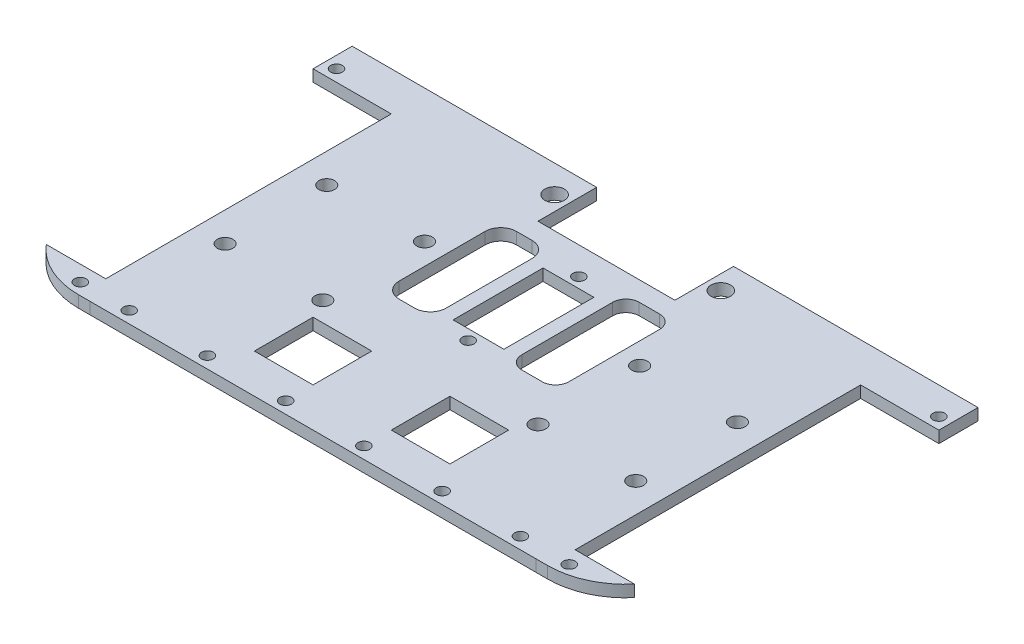
SolidWorks part; units mm, degrees
ref_plane "Alzado" through (0, 0, 0) normal (0, 0, 1) x (1, 0, 0)
ref_plane "Planta" through (0, 0, 0) normal (0, 1, 0) x (1, 0, 0)
ref_plane "Vista lateral" through (0, 0, 0) normal (1, 0, 0) x (0, 0, -1)
sketch "Croquis1" plane through (0, 0, 0) normal (0, 1, 0) x (1, 0, 0)
  line L0 (-80, 17.4769) -> (-80, -128.597) construction
  line L1 (0, 0) -> (-160, 0)
  line L2 (0, 0) -> (0, -70)
  line L3 (-20, -90) -> (-23, -90)
  line L4 (-160, 0) -> (-160, -70)
  line L5 (-101.3055, -36.199) -> (-73.3691, -36.199) construction
  line L6 (-86.5, -24.699) -> (-73.5, -24.699)
  line L7 (-86.5, -24.699) -> (-86.5, -47.699)
  line L8 (-86.5, -47.699) -> (-73.5, -47.699)
  line L9 (-73.5, -24.699) -> (-73.5, -47.699)
  line L10 (-137, -90) -> (-140, -90)
  line L12 (-137, -90) -> (-137, -89.999)
  line L13 (-137, -89.999) -> (-23, -89.999)
  line L14 (-23, -90) -> (-23, -89.999)
  line L15 (-89, -61.999) -> (-89, -81.749) construction
  line L16 (-105, -79.999) -> (-90, -79.999)
  line L17 (-105, -79.999) -> (-105, -64.999)
  line L18 (-105, -64.999) -> (-90, -64.999)
  line L19 (-90, -79.999) -> (-90, -64.999)
  line L20 (-55, -79.999) -> (-70, -79.999)
  line L21 (-55, -79.999) -> (-55, -64.999)
  line L22 (-55, -64.999) -> (-70, -64.999)
  line L23 (-70, -79.999) -> (-70, -64.999)
  circle A0 centre (-101.245, -7) radius 2.5
  circle A1 centre (-58.755, -7) radius 2.5
  circle A2 centre (-27.5, -60) radius 2
  circle A3 centre (-52.5, -60) radius 2
  circle A4 centre (-27.5, -34) radius 2
  circle A5 centre (-52.5, -34) radius 2
  circle A6 centre (-107.5, -34) radius 2
  circle A7 centre (-132.5, -34) radius 2
  circle A8 centre (-132.5, -60) radius 2
  circle A9 centre (-107.5, -60) radius 2
  circle A10 centre (-80, -22.054) radius 1.5
  circle A11 centre (-80, -50.344) radius 1.5
  arc A12 (0, -70) -> (-20, -90) centre (-20, -70) cw
  arc A13 (-140, -90) -> (-160, -70) centre (-140, -70) cw
  point P45 (-160, -90)
  dimension "D3" = 42.49
  dimension "D4" = 5
  dimension "D6" = 25
  dimension "D8" = 4
  dimension "D9" = 55
  dimension "D13" = 28.29
  dimension "D14" = 3
  dimension "D18" = 20
  dimension "D19" = 20
  dimension "D1" = 160
  dimension "D2" = 90
  dimension "D5" = 7
  dimension "D7" = 26
  dimension "D10" = 30
  dimension "D11" = 23
  dimension "D12" = 13
  dimension "D15" = 0.001
  dimension "D16" = 114
  dimension "D17" = 42.3
  dimension "D20" = 19
  dimension "D21" = 15
  dimension "D22" = 15
  dimension "D23" = 10
extrude "Saliente-Extruir1" add sketch "Croquis1" along normal blind 3
sketch "Croquis2" plane through (0, 3, 0) normal (0, 1, 0) x (1, 0, 0)
  line L0 (-160, 0) -> (-160, -70) construction
  line L1 (-160, -10) -> (-140, -10)
  line L2 (-160, -10) -> (-160, -82.999)
  line L3 (-160, -82.999) -> (-140, -82.999)
  line L4 (-140, -10) -> (-140, -82.999)
  line L5 (0, -70) -> (0, 0) construction
  line L6 (0, -10) -> (-20, -10)
  line L7 (0, -10) -> (0, -82.999)
  line L8 (0, -82.999) -> (-20, -82.999)
  line L9 (-20, -10) -> (-20, -82.999)
  line L10 (-80, 13.295) -> (-80, -109.5131) construction
  line L11 (0, 0) -> (-160, 0) construction
  line L12 (-137, -89.999) -> (-23, -89.999) construction
  dimension "D1" = 20
  dimension "D2" = 10
  dimension "D3" = 7
extrude "Cortar-Extruir1" cut sketch "Croquis2" against normal blind 10
sketch "Croquis3" plane through (0, 0, 0) normal (0, -1, 0) x (1, 0, 0)
  line L0 (0, 0) -> (-160, 0) construction
  line L1 (-97.5, 0) -> (-62.5, 0)
  line L2 (-97.5, 0) -> (-97.5, 15)
  line L3 (-97.5, 15) -> (-62.5, 15)
  line L4 (-62.5, 0) -> (-62.5, 15)
  line L5 (-80, 97.2712) -> (-80, -21.2749) construction
  line L6 (-20, 82.999) -> (-20, 10) construction
  line L7 (-140, 10) -> (-140, 82.999) construction
  dimension "D1" = 35
  dimension "D2" = 15
extrude "Cortar-Extruir2" cut sketch "Croquis3" against normal blind 10
sketch "Croquis4" plane through (0, 0, 0) normal (0, -1, 0) x (-1, 0, 0)
  line L0 (80, -96.2931) -> (80, 6.7064) construction
  line L1 (20, -82.999) -> (20, -10) construction
  line L2 (140, -10) -> (140, -82.999) construction
  line L3 (160, 0) -> (160, -10) construction
  line L4 (137, -89.999) -> (23, -89.999) construction
  line L5 (160, -10) -> (140, -10) construction
  circle A0 centre (157, -7) radius 1.5
  circle A1 centre (3, -7) radius 1.5
  circle A2 centre (30, -86.999) radius 1.5
  circle A3 centre (50, -86.999) radius 1.5
  circle A4 centre (70, -86.999) radius 1.5
  circle A5 centre (130, -86.999) radius 1.5
  circle A6 centre (90, -86.999) radius 1.5
  circle A7 centre (110, -86.999) radius 1.5
  circle A8 centre (142.5, -86.999) radius 1.5
  circle A9 centre (17.5, -86.999) radius 1.5
  dimension "D1" = 20
  dimension "D5" = 3
  dimension "D8" = 125
  dimension "D2" = 60
  dimension "D3" = 100
  dimension "D4" = 3
  dimension "D6" = 3
  dimension "D7" = 3
extrude "Cortar-Extruir3" cut sketch "Croquis4" against normal blind 10
sketch "Croquis5" plane through (0, 0, 0) normal (0, -1, 0) x (-1, 0, 0)
  line L0 (80, -99.9916) -> (80, 23.7881) construction
  line L1 (98, -50) -> (94, -50)
  line L2 (102, -46) -> (102, -24)
  line L3 (98, -20) -> (94, -20)
  line L4 (90, -46) -> (90, -24)
  line L5 (66.6138, -50) -> (61.3862, -50)
  line L6 (70, -46.6138) -> (70, -23.3862)
  line L7 (66.6138, -20) -> (61.3862, -20)
  line L8 (58, -46.6138) -> (58, -23.3862)
  line L9 (20, -82.999) -> (20, -10) construction
  line L10 (140, -10) -> (140, -82.999) construction
  line L11 (97.5, 0) -> (160, 0) construction
  arc A0 (94, -50) -> (90, -46) centre (94, -46) cw
  arc A1 (98, -50) -> (102, -46) centre (98, -46) ccw
  arc A2 (94, -20) -> (90, -24) centre (94, -24) ccw
  arc A3 (102, -24) -> (98, -20) centre (98, -24) ccw
  arc A4 (70, -23.3862) -> (66.6138, -20) centre (66.6138, -23.3862) ccw
  arc A5 (61.3862, -20) -> (58, -23.3862) centre (61.3862, -23.3862) ccw
  arc A6 (61.3862, -50) -> (58, -46.6138) centre (61.3862, -46.6138) cw
  arc A7 (66.6138, -50) -> (70, -46.6138) centre (66.6138, -46.6138) ccw
  point P18 (90, -50)
  point P21 (102, -50)
  point P26 (102, -20)
  dimension "D5" = 4
  dimension "D6" = 4
  dimension "D7" = 4
  dimension "D8" = 3.3862
  dimension "D9" = 3.3862
  dimension "D10" = 3.3862
  dimension "D11" = 3.3862
  dimension "D1" = 20
  dimension "D2" = 12
  dimension "D3" = 30
  dimension "D4" = 20
extrude "Cortar-Extruir4" cut sketch "Croquis5" against normal blind 10
